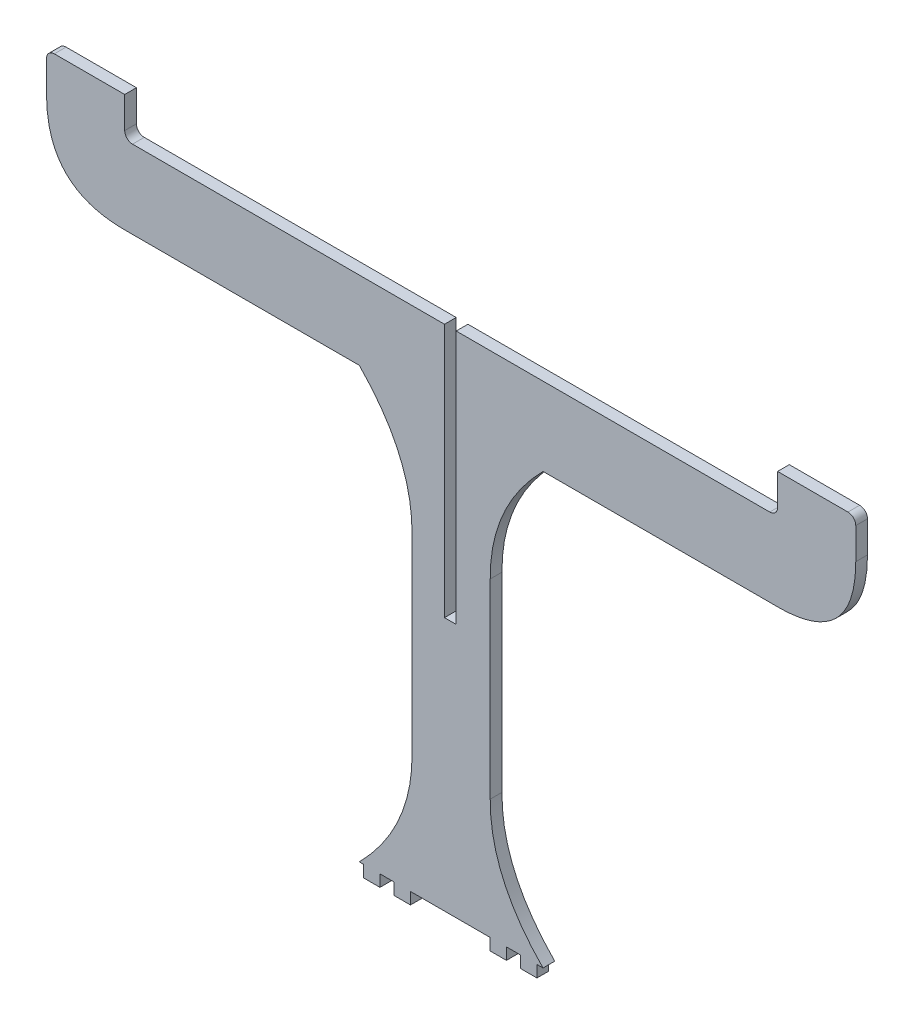
SolidWorks part; units mm, degrees
ref_plane "Přední rovina" through (0, 0, 0) normal (0, 0, 1) x (1, 0, 0)
ref_plane "Horní rovina" through (0, 0, 0) normal (0, 1, 0) x (1, 0, 0)
ref_plane "Pravá rovina" through (0, 0, 0) normal (1, 0, 0) x (0, 0, -1)
sketch "Skica1" plane through (0, 0, 0) normal (0, 0, 1) x (1, 0, 0)
  line L0 (-30.6426, 2.6943) -> (16.3574, 2.6943)
  line L1 (-7.1426, 2.6943) -> (-7.1426, -107.3057)
  line L2 (16.3574, -107.3057) -> (-30.6426, -107.3057)
  line L3 (-17.1426, 9.0001) -> (-17.1426, -176.0586) construction
  line L4 (27.2473, -27.3057) -> (-64.2445, -27.3057) construction
  line L5 (15.3668, -77.3057) -> (-64.2445, -77.3057) construction
  line L6 (-17.1426, -27.8784) -> (-17.1426, -76.656)
  line L7 (2.8574, -27.8784) -> (2.8574, -76.656)
  line L24 (-7.1426, -15.139) -> (-7.1426, 72.526) construction
  line L25 (10.652, -107.3057) -> (10.652, -110.3057)
  line L26 (10.652, -107.3057) -> (14.802, -107.3057)
  line L27 (14.802, -107.3057) -> (14.802, -110.3057)
  line L28 (10.652, -110.3057) -> (14.802, -110.3057)
  line L29 (2.852, -107.3057) -> (2.852, -110.3057)
  line L30 (2.852, -107.3057) -> (7.002, -107.3057)
  line L31 (7.002, -107.3057) -> (7.002, -110.3057)
  line L32 (2.852, -110.3057) -> (7.002, -110.3057)
  line L33 (-25.348, -110.3057) -> (-29.498, -110.3057)
  line L34 (-29.498, -107.3057) -> (-29.498, -110.3057)
  line L35 (-25.348, -107.3057) -> (-29.498, -107.3057)
  line L36 (-25.348, -107.3057) -> (-25.348, -110.3057)
  line L37 (-17.548, -110.3057) -> (-21.698, -110.3057)
  line L38 (-21.698, -107.3057) -> (-21.698, -110.3057)
  line L39 (-17.548, -107.3057) -> (-21.698, -107.3057)
  line L40 (-17.548, -107.3057) -> (-17.548, -110.3057)
  line L41 (-190.6426, 2.6943) -> (100.2644, 2.6943) construction
  line L42 (16.3574, 2.6943) -> (16.3574, 73.8241) construction
  line L43 (-30.6426, 73.8241) -> (-30.6426, 2.6943) construction
  line L44 (-110.6426, 2.6943) -> (-110.6426, 52.9232) construction
  line L45 (-190.6426, 32.6943) -> (86.9117, 32.6943) construction
  line L46 (-30.6426, 2.6943) -> (-90.6426, 2.6943)
  line L47 (-90.6426, -13.7924) -> (-90.6426, 96.8534) construction
  line L48 (-70.6426, -7.8313) -> (-70.6426, 84.4343) construction
  line L49 (-194.5635, 22.6943) -> (-7.1426, 22.6943) construction
  line L50 (-108.6426, 32.6943) -> (-90.6426, 32.6943)
  line L51 (-90.6426, 32.6943) -> (-90.6426, 24.6943)
  line L52 (-110.6426, 22.6943) -> (-110.6426, 30.6943)
  line L53 (16.3574, 2.6943) -> (76.3574, 2.6943)
  line L54 (-110.6426, 22.6943) -> (-110.6426, 2.6943) construction
  line L55 (76.3574, 32.6943) -> (76.3574, 24.6943)
  line L56 (-110.6426, 2.6943) -> (-90.6426, 2.6943) construction
  line L57 (94.3574, 32.6943) -> (76.3574, 32.6943)
  line L58 (-88.6426, 22.6943) -> (74.3574, 22.6943)
  line L59 (-7.1426, 22.6943) -> (-7.1426, 2.6943)
  line L60 (96.3574, 22.6943) -> (96.3574, 30.6943)
  line L61 (96.3574, 22.6943) -> (96.3574, 2.6943) construction
  line L62 (96.3574, 2.6943) -> (76.3574, 2.6943) construction
  arc A0 (74.3574, 22.6943) -> (76.3574, 24.6943) centre (74.3574, 24.6943) ccw
  arc A1 (-88.6426, 22.6943) -> (-90.6426, 24.6943) centre (-88.6426, 24.6943) cw
  arc A2 (-110.6426, 30.6943) -> (-108.6426, 32.6943) centre (-108.6426, 30.6943) cw
  arc A3 (96.3574, 30.6943) -> (94.3574, 32.6943) centre (94.3574, 30.6943) ccw
  spline S0 degree 2 poles (-30.6426, 2.6943) (-17.0251, -11.1181) (-17.1426, -27.8784) knots 0 0 0 1 1 1
  spline S1 degree 2 poles (-30.6426, -107.3057) (-17.0093, -93.4583) (-17.1426, -76.656) knots 0 0 0 1 1 1
  spline S2 degree 2 poles (16.3574, 2.6943) (2.7399, -11.1181) (2.8574, -27.8784) knots 0 0 0 1 1 1
  spline S3 degree 2 poles (16.3574, -107.3057) (2.724, -93.4583) (2.8574, -76.656) knots 0 0 0 1 1 1
  spline S4 degree 2 poles (-110.6426, 22.6943) (-110.6426, 2.6943) (-90.6426, 2.6943) knots 0 0 0 1 1 1
  spline S5 degree 2 poles (96.3574, 22.6943) (96.3574, 2.6943) (76.3574, 2.6943) knots 0 0 0 1 1 1
  point P29 (-110.6426, 2.6943)
  point P37 (-110.6426, 22.6943)
  point P54 (-110.6426, 32.6943)
  point P55 (-90.6426, 32.6943)
  point P56 (-90.6426, 22.6943)
  point P70 (-90.6426, 22.6943)
  point P73 (-110.6426, 32.6943)
  dimension "D15" = 60
  dimension "D17" = 2
  dimension "D18" = 2
  dimension "D1" = 110
  dimension "D2" = 23.5
  dimension "D3" = 30
  dimension "D4" = 30
  dimension "D5" = 30.6498
  dimension "D6" = 23.5
  dimension "D7" = 47
  dimension "D8" = 30
  dimension "D9" = 30
  dimension "D10" = 20
  dimension "D11" = 80
  dimension "D12" = 20
  dimension "D13" = 40
  dimension "D14" = 10
extrude "Přidat vysunutím2" add sketch "Skica1" along normal blind 3
sketch "Skica2" plane through (0, 0, 0) normal (0, 0, -1) x (-1, 0, 0)
  line L0 (7.348, -129.2799) -> (7.348, 48.5683) construction
  line L1 (50.2587, -42.3057) -> (-73.7805, -42.3057) construction
  line L2 (-2.852, -107.3057) -> (17.548, -107.3057) construction
  line L5 (8.848, -107.3057) -> (5.848, -107.3057)
  line L8 (8.848, 22.6943) -> (5.848, 22.6943)
  line L9 (8.848, 22.6943) -> (8.848, -42.3057)
  line L10 (8.848, -42.3057) -> (5.848, -42.3057)
  line L11 (5.848, 22.6943) -> (5.848, -42.3057)
  line L12 (8.848, 22.6943) -> (5.848, -42.3057) construction
  line L13 (8.848, -42.3057) -> (5.848, 22.6943) construction
  point P5 (7.348, -84.8057)
  point P8 (7.348, -9.8057)
  dimension "D1" = 65
  dimension "D2" = 130
  dimension "D4" = 3
  dimension "D5" = 3
extrude "Odebrat vysunutím3" cut sketch "Skica2" against normal blind 3 contours L11 L10 L9 L8
